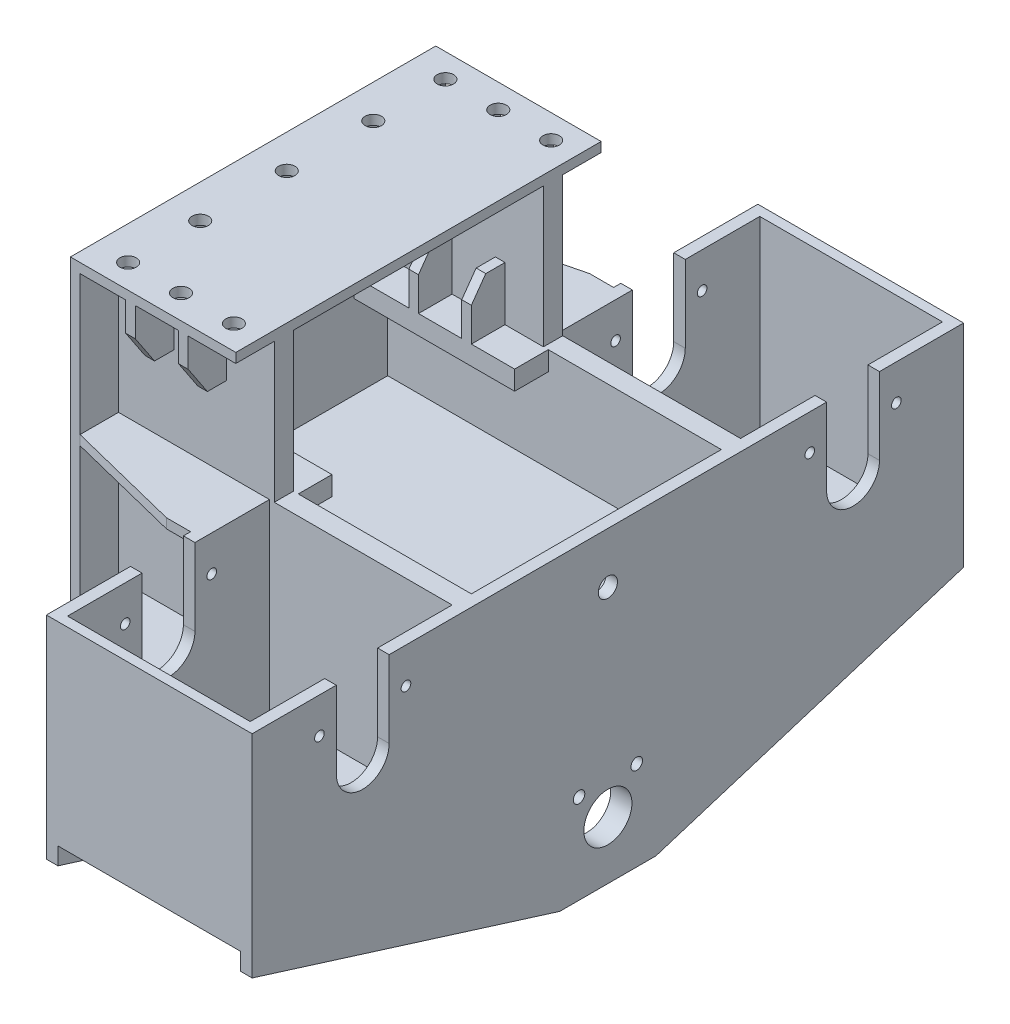
SolidWorks part; units mm, degrees
ref_plane "前视基准面" through (0, 0, 0) normal (0, 0, 1) x (1, 0, 0)
ref_plane "上视基准面" through (0, 0, 0) normal (0, 1, 0) x (1, 0, 0)
ref_plane "右视基准面" through (0, 0, 0) normal (1, 0, 0) x (0, 0, -1)
sketch "草图1" plane through (0, 0, 0) normal (0, 1, 0) x (1, 0, 0)
  line L1 (0, 0) -> (172, 0)
  line L2 (0, 0) -> (0, 380)
  line L3 (0, 380) -> (172, 380)
  line L4 (172, 0) -> (172, 380)
  dimension "D1" = 172
  dimension "D2" = 380
extrude "凸台-拉伸1" add sketch "草图1" along normal blind 10
sketch "草图2" plane through (0, 10, 0) normal (0, 1, 0) x (1, 0, 0)
  line L0 (90, -975) -> (90, 49025) construction
  line L2 (35, -725.1977) -> (35, 49274.8023) construction
  line L3 (145, -739.4867) -> (145, 49260.5133) construction
  line L4 (-828, 190) -> (49172, 190) construction
  line L5 (172, 0) -> (172, 380) construction
  line L6 (-846.2824, 355) -> (49153.7176, 355) construction
  line L7 (-846.2824, 280) -> (49153.7176, 280) construction
  line L8 (-845.0399, 100) -> (49154.9601, 100) construction
  line L9 (-850.01, 25) -> (49149.99, 25) construction
  circle A0 centre (35, 355) radius 8.5
  circle A1 centre (35, 280) radius 8.5
  circle A2 centre (35, 190) radius 8.5
  circle A3 centre (35, 100) radius 8.5
  circle A4 centre (35, 25) radius 8.5
  circle A5 centre (90, 25) radius 8.5
  circle A6 centre (145, 25) radius 8.5
  circle A7 centre (90, 355) radius 8.5
  circle A8 centre (145, 355) radius 8.5
  point P14 (172, 190)
  dimension "D7" = 17
  dimension "D1" = 55
  dimension "D2" = 55
  dimension "D3" = 90
  dimension "D4" = 90
  dimension "D5" = 165
  dimension "D6" = 165
  dimension "D8" = 27
extrude "切除-拉伸1" cut sketch "草图2" against normal blind 10
sketch "草图3" plane through (0, 0, 0) normal (0, -1, 0) x (1, 0, 0)
  line L0 (172, -380) -> (0, -380) construction
  line L1 (0, 0) -> (10, 0)
  line L2 (0, 0) -> (0, -380)
  line L3 (0, -380) -> (10, -380)
  line L4 (10, 0) -> (10, -380)
  dimension "D1" = 10
extrude "凸台-拉伸2" add sketch "草图3" along normal blind 347
sketch "草图4" plane through (0, 0, 0) normal (-1, 0, 0) x (0, 0, 1)
  line L0 (-190, -990) -> (-190, 49010) construction
  line L1 (-380, 10) -> (0, 10) construction
  line L2 (-235.5, -1154.5473) -> (-235.5, 48845.4527) construction
  line L3 (-144.5, -1205.566) -> (-144.5, 48794.434) construction
  line L4 (-235.5, -347) -> (-144.5, -347)
  line L6 (-144.5, -347) -> (-190, -324.9687)
  line L7 (-190, -324.9687) -> (-235.5, -347)
  line L8 (0, -347) -> (-380, -347) construction
  line L9 (-190, -382.9687) -> (-144.5, -347) construction
  line L10 (-247, -1018.4029) -> (-247, 48981.5971) construction
  line L11 (-133, -1019.3061) -> (-133, 48980.6939) construction
  line L12 (-1052.4558, -75) -> (48947.5442, -75) construction
  line L13 (-1061.67, -118) -> (48938.33, -118) construction
  circle A0 centre (-133, -75) radius 7
  circle A1 centre (-247, -75) radius 7
  circle A2 centre (-133, -118) radius 7
  circle A3 centre (-247, -118) radius 7
  point P5 (-190, 10)
  dimension "D9" = 14
  dimension "D1" = 45.5
  dimension "D2" = 45.5
  dimension "D3" = 58
  dimension "D4" = 58
  dimension "D5" = 57
  dimension "D6" = 57
  dimension "D7" = 128
  dimension "D8" = 43
extrude "切除-拉伸2" cut sketch "草图4" against normal blind 10
sketch "草图5" plane through (0, 0, 0) normal (0, -1, 0) x (1, 0, 0)
  line L0 (10, -380) -> (10, 0) construction
  line L1 (10, -40) -> (172, -40)
  line L2 (10, -40) -> (10, -60)
  line L3 (10, -60) -> (172, -60)
  line L4 (172, -40) -> (172, -60)
  line L5 (172, 0) -> (172, -380) construction
  line L6 (-828, -190) -> (49172, -190) construction
  line L7 (10, -320) -> (172, -320)
  line L8 (10, -320) -> (10, -340)
  line L9 (10, -340) -> (172, -340)
  line L10 (172, -320) -> (172, -340)
  point P15 (172, -190)
  dimension "D1" = 20
  dimension "D2" = 20
  dimension "D3" = 130
  dimension "D4" = 130
extrude "凸台-拉伸3" add sketch "草图5" along normal blind 347
sketch "草图6" plane through (172, 0, 0) normal (1, 0, 0) x (0, 0, -1)
  line L0 (40, -347) -> (40, 0) construction
  line L1 (40, -145) -> (60, -145)
  line L2 (40, -145) -> (40, -430)
  line L3 (40, -430) -> (60, -430)
  line L4 (60, -145) -> (60, -430)
  line L5 (60, -347) -> (60, 0) construction
  line L6 (320, -145) -> (340, -145)
  line L7 (320, -145) -> (320, -430)
  line L8 (320, -430) -> (340, -430)
  line L9 (340, -145) -> (340, -430)
  line L10 (320, -347) -> (320, 0) construction
  line L11 (340, -347) -> (340, 0) construction
  line L12 (60, -347) -> (40, -347) construction
  dimension "D1" = 285
  dimension "D2" = 83
extrude "凸台-拉伸4" add sketch "草图6" along normal blind 185
sketch "草图9" plane through (0, -347, 0) normal (0, -1, 0) x (1, 0, 0)
  line L0 (10, -340) -> (172, -340) construction
  line L1 (167, -340) -> (172, -340)
  line L2 (167, -340) -> (167, -320)
  line L3 (167, -320) -> (172, -320)
  line L4 (172, -340) -> (172, -320)
  line L5 (172, -40) -> (10, -40) construction
  line L6 (172, -60) -> (167, -60)
  line L7 (172, -60) -> (172, -40)
  line L8 (172, -40) -> (167, -40)
  line L9 (167, -60) -> (167, -40)
  dimension "D1" = 5
  dimension "D2" = 5
extrude "凸台-拉伸6" add sketch "草图9" along normal blind 83
sketch "草图7" plane through (357, 0, 0) normal (1, 0, 0) x (0, 0, -1)
  line L0 (190, -1278.79) -> (190, 48721.21) construction
  line L1 (60, -347) -> (60, 0) construction
  line L2 (320, -145) -> (320, -430) construction
  line L3 (-37.5, -145) -> (417.5, -145)
  line L4 (417.5, -145) -> (417.5, -225)
  line L5 (-37.5, -145) -> (-37.5, -225)
  line L6 (-65, -1199.5555) -> (-65, 48800.4445) construction
  line L7 (445, -1213.2414) -> (445, 48786.7586) construction
  line L8 (340, -145) -> (320, -145) construction
  line L9 (472.5, -145) -> (472.5, -225)
  line L10 (-92.5, -145) -> (-92.5, -225)
  line L11 (472.5, -145) -> (560, -145)
  line L12 (560, -145) -> (560, -365)
  line L13 (-92.5, -145) -> (-180, -145)
  line L14 (-180, -145) -> (-180, -365)
  line L15 (-180, -365) -> (140, -465)
  line L16 (140, -465) -> (240, -465)
  line L17 (240, -465) -> (560, -365)
  line L18 (-407.1755, -182) -> (49592.8245, -182) construction
  arc A0 (-92.5, -225) -> (-37.5, -225) centre (-65, -225) ccw
  arc A1 (417.5, -225) -> (472.5, -225) centre (445, -225) ccw
  circle A2 centre (490, -182) radius 5
  circle A3 centre (400, -182) radius 5
  circle A4 centre (-110, -182) radius 5
  circle A5 centre (-20, -182) radius 5
  circle A6 centre (190, -198) radius 10
  circle A7 centre (190, -405) radius 25
  circle A8 centre (160, -372) radius 6
  circle A9 centre (220, -372) radius 6
  dimension "D14" = 10
  dimension "D17" = 20
  dimension "D19" = 50
  dimension "D21" = 12
  dimension "D1" = 255
  dimension "D2" = 255
  dimension "D3" = 27.5
  dimension "D4" = 27.5
  dimension "D5" = 80
  dimension "D6" = 80
  dimension "D7" = 370
  dimension "D8" = 370
  dimension "D9" = 220
  dimension "D10" = 320
  dimension "D11" = 50
  dimension "D12" = 50
  dimension "D13" = 37
  dimension "D15" = 90
  dimension "D16" = 90
  dimension "D18" = 53
  dimension "D20" = 180
  dimension "D22" = 60
  dimension "D23" = 33
extrude "凸台-拉伸5" add sketch "草图7" along normal blind 12
pattern_linear "阵列(线性)1" count 2 spacing 202 along (-1, 0, 0) of "凸台-拉伸5"
sketch "草图8" plane through (167, 0, 0) normal (1, 0, 0) x (0, 0, -1)
  line L0 (190, -1145) -> (190, 48855) construction
  line L1 (320, -145) -> (60, -145) construction
  line L2 (60, -145) -> (320, -145)
  line L3 (320, -145) -> (320, -347)
  line L4 (320, -145) -> (320, -430) construction
  line L5 (60, -145) -> (60, -347)
  line L6 (60, -430) -> (60, -145) construction
  line L7 (60, -347) -> (115, -347)
  line L8 (115, -347) -> (190, -325)
  line L9 (265, -347) -> (320, -347)
  line L10 (190, -325) -> (265, -347)
  point P5 (190, -145)
  dimension "D1" = 202
  dimension "D2" = 202
  dimension "D3" = 75
  dimension "D4" = 75
  dimension "D5" = 22
extrude "切除-拉伸3" cut sketch "草图8" against normal blind 12
sketch "草图11" plane through (10, 0, 0) normal (1, 0, 0) x (0, 0, -1)
  line L0 (60, -335) -> (115, -335)
  line L1 (60, -145) -> (60, 0) construction
  line L2 (115, -335) -> (190, -313)
  line L3 (190, -313) -> (265, -335)
  line L4 (265, -335) -> (320, -335)
  line L5 (320, -347) -> (320, 0) construction
  line L6 (320, -335) -> (320, -347)
  line L7 (320, -347) -> (265, -347)
  line L8 (265, -347) -> (190, -325)
  line L9 (190, -325) -> (115, -347)
  line L10 (115, -347) -> (60, -347)
  line L11 (60, -347) -> (60, -335)
  line L12 (60, -347) -> (115, -347) construction
  line L13 (265, -347) -> (320, -347) construction
  dimension "D1" = 12
  dimension "D2" = 12
extrude "凸台-拉伸7" add sketch "草图11" along normal blind 347
sketch "草图13" plane through (369, 0, 0) normal (1, 0, 0) x (0, 0, -1)
  line L0 (60, -335) -> (60, 0) construction
  line L1 (60, -252) -> (320, -252)
  line L2 (60, -252) -> (60, -262)
  line L3 (60, -262) -> (320, -262)
  line L4 (320, -252) -> (320, -262)
  line L5 (60, -145) -> (60, 0) construction
  line L6 (320, -145) -> (320, 0) construction
  line L7 (-1037.5, -225) -> (48962.5, -225) construction
  dimension "D1" = 10
  dimension "D2" = 27
extrude "凸台-拉伸10" add sketch "草图13" against normal blind 359
sketch "草图14" plane through (0, -145, 0) normal (0, 1, 0) x (1, 0, 0)
  line L0 (357, -92.5) -> (357, -180) construction
  line L1 (167, -180) -> (357, -180)
  line L2 (167, -180) -> (167, -170)
  line L3 (167, -170) -> (357, -170)
  line L4 (357, -180) -> (357, -170)
  line L5 (167, 560) -> (167, 472.5) construction
  line L6 (357, 560) -> (167, 560)
  line L7 (357, 560) -> (357, 550)
  line L8 (357, 550) -> (167, 550)
  line L9 (167, 560) -> (167, 550)
  dimension "D1" = 10
  dimension "D2" = 10
extrude "凸台-拉伸11" add sketch "草图14" against normal blind 190
sketch "草图15" plane through (0, -335, 0) normal (0, -1, 0) x (-1, 0, 0)
  line L0 (-357, -180) -> (-357, 140) construction
  line L1 (-167, -180) -> (-357, -180)
  line L2 (-167, -180) -> (-167, 40)
  line L3 (-167, 40) -> (-357, 40)
  line L4 (-357, -180) -> (-357, 40)
  line L5 (-357, 240) -> (-357, 560) construction
  line L6 (-167, 560) -> (-357, 560)
  line L7 (-167, 560) -> (-167, 340)
  line L8 (-167, 340) -> (-357, 340)
  line L9 (-357, 560) -> (-357, 340)
  line L10 (-357, 340) -> (-167, 340) construction
  line L11 (-357, 40) -> (-167, 40) construction
extrude "凸台-拉伸12" add sketch "草图15" along normal blind 12
sketch "草图16" plane through (0, -347, 0) normal (0, -1, 0) x (-1, 0, 0)
  line L0 (-155, 40) -> (-10, 40) construction
  line L1 (-10, 40) -> (-155, 40)
  line L2 (-10, 40) -> (-10, 50)
  line L3 (-10, 50) -> (-155, 50)
  line L4 (-155, 40) -> (-155, 50)
  line L5 (-155, 115) -> (-155, 40) construction
  line L7 (-155, 340) -> (-10, 340)
  line L8 (-155, 340) -> (-155, 330)
  line L9 (-155, 330) -> (-10, 330)
  line L10 (-10, 340) -> (-10, 330)
  dimension "D1" = 10
  dimension "D2" = 10
  dimension "D3" = 145
  dimension "D4" = 145
extrude "凸台-拉伸13" add sketch "草图16" along normal blind 80
sketch "草图17" plane through (0, 0, -40) normal (0, 0, 1) x (1, 0, 0)
  line L0 (10, -427) -> (10, -397)
  line L1 (10, -427) -> (10, -347) construction
  line L2 (10, -397) -> (55, -427)
  line L3 (155, -427) -> (10, -427) construction
  line L4 (55, -427) -> (10, -427)
  dimension "D1" = 45
  dimension "D2" = 30
extrude "切除-拉伸4" cut sketch "草图17" against normal through all
sketch "草图18" plane through (155, 0, 0) normal (-1, 0, 0) x (0, 0, 1)
  line L0 (-1417.5, -225) -> (48582.5, -225) construction
  line L1 (-40, -145) -> (30, -145)
  line L2 (-40, -145) -> (-40, -155)
  line L3 (-40, -155) -> (30, -155)
  line L4 (30, -145) -> (30, -155)
  line L5 (-340, -145) -> (-410, -145)
  line L6 (-340, -145) -> (-340, -155)
  line L7 (-340, -155) -> (-410, -155)
  line L8 (-410, -145) -> (-410, -155)
  line L10 (-410, -295) -> (-340, -295)
  line L11 (-410, -295) -> (-410, -305)
  line L12 (-410, -305) -> (-340, -305)
  line L13 (-340, -295) -> (-340, -305)
  line L14 (-40, -295) -> (30, -295)
  line L15 (-40, -295) -> (-40, -305)
  line L16 (-40, -305) -> (30, -305)
  line L17 (30, -295) -> (30, -305)
  dimension "D1" = 10
  dimension "D2" = 70
  dimension "D3" = 70
  dimension "D4" = 10
extrude "凸台-拉伸14" add sketch "草图18" along normal blind 145
sketch "草图19" plane through (0, -305, 0) normal (0, -1, 0) x (-1, 0, 0)
  line L0 (-10, -30) -> (-10, 0)
  line L1 (-10, 0) -> (-130, -30)
  line L3 (-130, -30) -> (-10, -30)
  line L4 (-10, 410) -> (-10, 380)
  line L5 (-10, 380) -> (-130, 410)
  line L7 (-130, 410) -> (-10, 410)
  line L8 (-10, 410) -> (-10, 380) construction
  line L9 (-10, 410) -> (-155, 410) construction
  line L10 (-172, 380) -> (-10, 380) construction
  line L11 (-10, 0) -> (-10, -30) construction
  line L12 (-10, 0) -> (-172, 0) construction
  line L13 (-10, -30) -> (-155, -30) construction
  dimension "D1" = 120
  dimension "D2" = 120
extrude "切除-拉伸5" cut sketch "草图19" against normal through all
sketch "草图20" plane through (10, 0, 0) normal (1, 0, 0) x (0, 0, -1)
  line L0 (60, -252) -> (60, 0) construction
  line L1 (60, -145) -> (95, -145)
  line L2 (60, -145) -> (60, -165)
  line L3 (60, -165) -> (95, -165)
  line L4 (95, -145) -> (95, -165)
  line L5 (320, -252) -> (320, 0) construction
  line L6 (320, -145) -> (285, -145)
  line L7 (320, -145) -> (320, -165)
  line L8 (320, -165) -> (285, -165)
  line L9 (285, -145) -> (285, -165)
  dimension "D1" = 35
  dimension "D2" = 20
extrude "凸台-拉伸15" add sketch "草图20" along normal blind 167
sketch "草图21" plane through (0, 0, -320) normal (0, 0, 1) x (1, 0, 0)
  line L0 (172, -145) -> (10, -145) construction
  line L1 (67, -89) -> (77, -89)
  line L2 (67, -89) -> (67, -145)
  line L3 (67, -145) -> (77, -145)
  line L4 (77, -89) -> (77, -145)
  line L5 (10, -145) -> (10, 0) construction
  line L6 (122, -89) -> (132, -89)
  line L7 (122, -89) -> (122, -145)
  line L8 (122, -145) -> (132, -145)
  line L9 (132, -89) -> (132, -145)
  dimension "D1" = 57
  dimension "D2" = 10
  dimension "D3" = 56
  dimension "D4" = 45
extrude "凸台-拉伸16" add sketch "草图21" along normal blind 35
sketch "草图22" plane through (0, 0, -60) normal (0, 0, -1) x (-1, 0, 0)
  line L0 (-172, -145) -> (-10, -145) construction
  line L1 (-122, -145) -> (-132, -145)
  line L2 (-122, -145) -> (-122, -89)
  line L3 (-122, -89) -> (-132, -89)
  line L4 (-132, -145) -> (-132, -89)
  line L5 (-10, -145) -> (-10, 0) construction
  line L6 (-67, -145) -> (-77, -145)
  line L7 (-67, -145) -> (-67, -89)
  line L8 (-67, -89) -> (-77, -89)
  line L9 (-77, -145) -> (-77, -89)
  dimension "D1" = 10
  dimension "D2" = 56
  dimension "D3" = 45
  dimension "D4" = 57
extrude "凸台-拉伸17" add sketch "草图22" along normal blind 35
sketch "草图23" plane through (132, 0, 0) normal (1, 0, 0) x (0, 0, -1)
  line L0 (95, -89) -> (80, -89)
  line L1 (95, -89) -> (60, -89) construction
  line L2 (80, -89) -> (95, -110)
  line L3 (95, -89) -> (95, -145) construction
  line L4 (95, -110) -> (95, -89)
  line L5 (285, -89) -> (300, -89)
  line L6 (285, -89) -> (320, -89) construction
  line L7 (300, -89) -> (285, -110)
  line L8 (285, -145) -> (285, -89) construction
  line L9 (285, -110) -> (285, -89)
  dimension "D1" = 15
  dimension "D2" = 15
  dimension "D3" = 21
  dimension "D4" = 21
extrude "切除-拉伸6" cut sketch "草图23" against normal blind 65
sketch "草图24" plane through (0, 0, 0) normal (0, -1, 0) x (1, 0, 0)
  line L0 (10, -320) -> (10, -60) construction
  line L1 (10, -140) -> (60, -140)
  line L3 (-969, -190) -> (49031, -190) construction
  line L5 (10, -140) -> (10, -150)
  line L6 (10, -150) -> (60, -150)
  line L7 (60, -140) -> (60, -150)
  line L9 (10, -230) -> (60, -230)
  line L10 (10, -230) -> (10, -240)
  line L11 (10, -240) -> (60, -240)
  line L12 (60, -230) -> (60, -240)
  dimension "D1" = 10
  dimension "D2" = 10
  dimension "D3" = 50
  dimension "D4" = 50
  dimension "D5" = 40
  dimension "D6" = 40
extrude "凸台-拉伸18" add sketch "草图24" along normal blind 50
sketch "草图25" plane through (0, 0, -240) normal (0, 0, -1) x (-1, 0, 0)
  line L0 (-60, -50) -> (-60, -20)
  line L1 (-60, -50) -> (-60, 0) construction
  line L2 (-60, -20) -> (-30, -50)
  line L3 (-10, -50) -> (-60, -50) construction
  line L4 (-30, -50) -> (-60, -50)
  dimension "D1" = 30
  dimension "D2" = 30
extrude "切除-拉伸7" cut sketch "草图25" against normal blind 100
sketch "草图26" plane through (0, 0, 0) normal (0, -1, 0) x (1, 0, 0)
  line L0 (90, -1355) -> (90, 48645) construction
  line L1 (35, -1355) -> (35, 48645) construction
  line L2 (145, -1355) -> (145, 48645) construction
  line L4 (10, -340) -> (172, -340) construction
  line L5 (122.5, -340) -> (112.5, -340)
  line L6 (122.5, -340) -> (122.5, -380)
  line L7 (122.5, -380) -> (112.5, -380)
  line L8 (112.5, -340) -> (112.5, -380)
  line L9 (172, -380) -> (10, -380) construction
  line L10 (10, 0) -> (172, 0) construction
  line L11 (67.5, -340) -> (57.5, -340)
  line L12 (67.5, -340) -> (67.5, -380)
  line L13 (67.5, -380) -> (57.5, -380)
  line L14 (57.5, -340) -> (57.5, -380)
  line L15 (122.5, 0) -> (112.5, 0)
  line L16 (122.5, 0) -> (122.5, -40)
  line L17 (122.5, -40) -> (112.5, -40)
  line L18 (112.5, 0) -> (112.5, -40)
  line L19 (172, -40) -> (10, -40) construction
  line L21 (67.5, 0) -> (57.5, 0)
  line L22 (67.5, 0) -> (67.5, -40)
  line L23 (67.5, -40) -> (57.5, -40)
  line L24 (57.5, 0) -> (57.5, -40)
  dimension "D1" = 10
  dimension "D2" = 10
  dimension "D3" = 10
  dimension "D4" = 10
  dimension "D5" = 22.5
  dimension "D6" = 22.5
  dimension "D7" = 22.5
  dimension "D8" = 22.5
extrude "凸台-拉伸19" add sketch "草图26" along normal blind 60
sketch "草图27" plane through (57.5, 0, 0) normal (-1, 0, 0) x (0, 0, 1)
  line L0 (0, -60) -> (-20, -60)
  line L1 (0, -60) -> (-40, -60) construction
  line L2 (-20, -60) -> (0, -30)
  line L3 (0, -60) -> (0, 0) construction
  line L4 (0, -30) -> (0, -60)
  line L5 (-380, -60) -> (-360, -60)
  line L6 (-340, -60) -> (-380, -60) construction
  line L7 (-360, -60) -> (-380, -30)
  line L8 (-380, -60) -> (-380, 0) construction
  line L9 (-380, -30) -> (-380, -60)
extrude "切除-拉伸8" cut sketch "草图27" against normal blind 65
sketch "草图28" plane through (357, 0, 0) normal (-1, 0, 0) x (0, 0, 1)
  line L0 (-140, -465) -> (-240, -465) construction
  line L1 (-226.0555, -465) -> (-153.9445, -465)
  circle A0 centre (-190, -405) radius 25
  circle A1 centre (-190, -405) radius 25 construction
  circle A2 centre (-220, -372) radius 6
  circle A3 centre (-160, -372) radius 6
  circle A4 centre (-220, -372) radius 6 construction
  circle A5 centre (-160, -372) radius 6 construction
  arc A6 (-153.9445, -465) -> (-226.0555, -465) centre (-190, -405) ccw
  dimension "D1" = 70
extrude "凸台-拉伸20" add sketch "草图28" along normal blind 10
pattern_linear "阵列(线性)2" count 2 spacing 180 along (-1, 0, 0) of "凸台-拉伸20"
